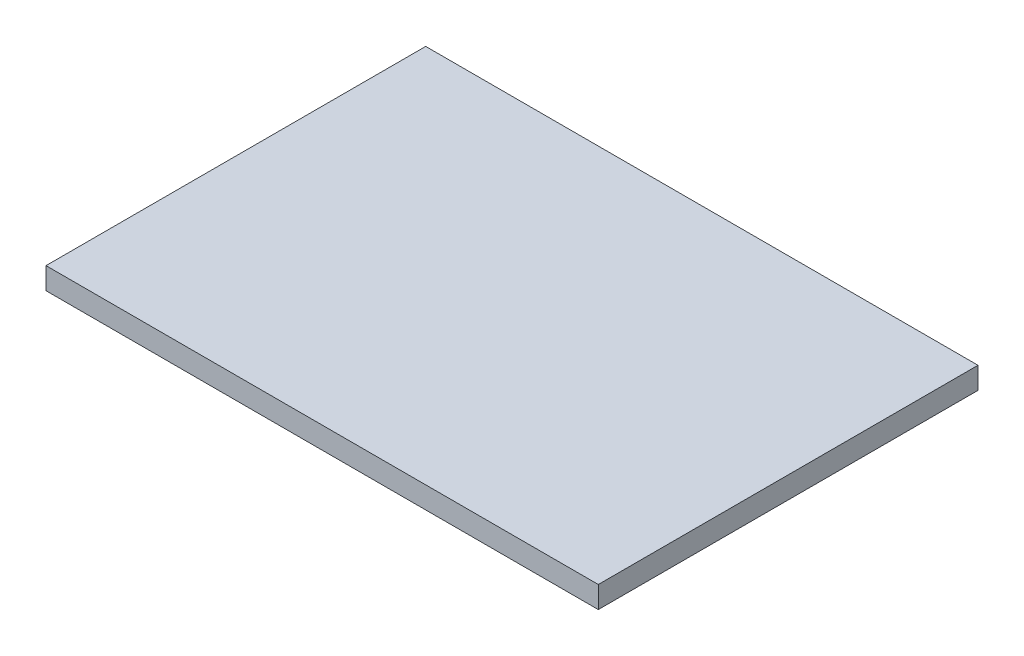
SolidWorks part; units mm, degrees
ref_plane "Front" through (0, 0, 0) normal (0, 0, 1) x (1, 0, 0)
ref_plane "Top" through (0, 0, 0) normal (0, 1, 0) x (1, 0, 0)
ref_plane "Right" through (0, 0, 0) normal (1, 0, 0) x (0, 0, -1)
sketch "Sketch1" plane through (0, 0, 0) normal (0, 1, 0) x (1, 0, 0)
  line L1 (406.4, -279.4) -> (-406.4, -279.4)
  line L2 (406.4, -279.4) -> (406.4, 279.4)
  line L3 (406.4, 279.4) -> (-406.4, 279.4)
  line L4 (-406.4, -279.4) -> (-406.4, 279.4)
  line L5 (406.4, -279.4) -> (-406.4, 279.4) construction
  line L6 (406.4, 279.4) -> (-406.4, -279.4) construction
  point P0 (0, 0)
  dimension "D1" = 812.8
  dimension "D2" = 558.8
extrude "Boss-Extrude1" add sketch "Sketch1" along normal blind 32
